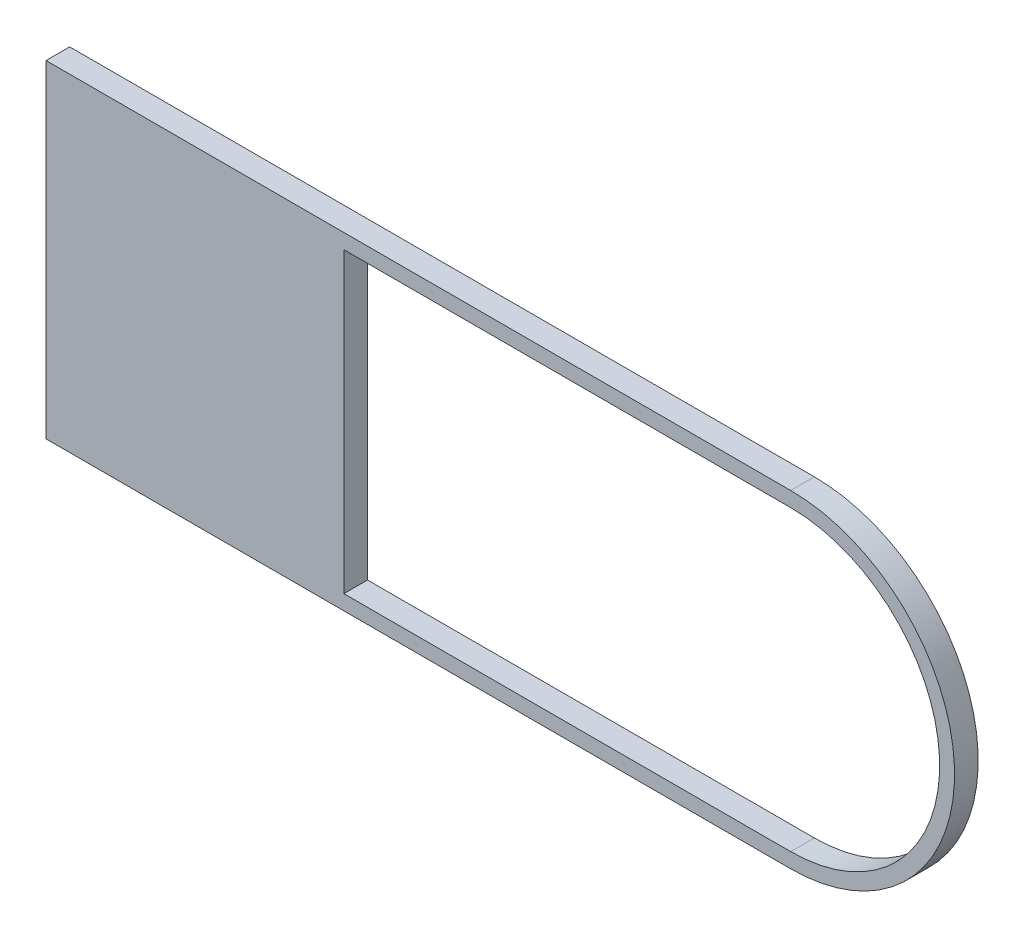
SolidWorks part; units mm, degrees
material "Acrylic (Medium-high impact)"
ref_plane "Front Plane" through (0, 0, 0) normal (0, 0, 1) x (1, 0, 0)
ref_plane "Top Plane" through (0, 0, 0) normal (0, 1, 0) x (1, 0, 0)
ref_plane "Right Plane" through (0, 0, 0) normal (1, 0, 0) x (0, 0, -1)
sketch "Sketch1" plane through (0, 0, 0) normal (0, 0, 1) x (1, 0, 0)
  line L3 (0, 0) -> (100, 0)
  line L4 (0, 0) -> (0, 44)
  line L5 (0, 44) -> (100, 44)
  line L6 (40, 2) -> (40, 42)
  line L7 (40, 42) -> (100, 42)
  line L8 (40, 2) -> (100, 2)
  arc A1 (100, 44) -> (100, 0) centre (100, 22) cw
  arc A2 (100, 2) -> (100, 42) centre (100, 22) ccw
  point P13 (120, 22)
  dimension "D1" = 20
  dimension "D2" = 2
  dimension "D3" = 2
  dimension "D4" = 40
  dimension "D5" = 120
extrude "Boss-Extrude1" add sketch "Sketch1" along normal blind 3.175
